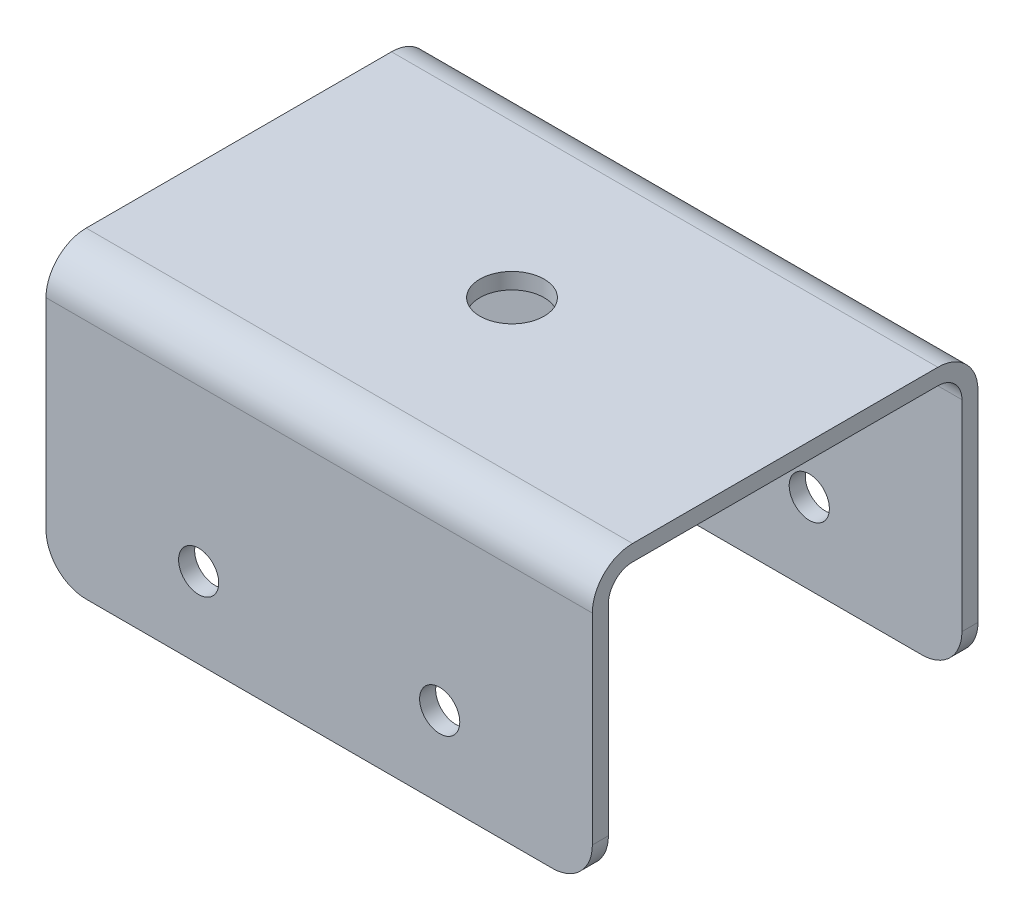
SolidWorks part; units mm, degrees
ref_plane "Front Plane" through (0, 0, 0) normal (0, 0, 1) x (1, 0, 0)
ref_plane "Top Plane" through (0, 0, 0) normal (0, 1, 0) x (1, 0, 0)
ref_plane "Right Plane" through (0, 0, 0) normal (1, 0, 0) x (0, 0, -1)
sketch "Sketch1" plane through (0, 0, 0) normal (0, 1, 0) x (1, 0, 0)
  line L1 (-34, 24) -> (34, 24)
  line L2 (-34, 24) -> (-34, -24)
  line L3 (-34, -24) -> (34, -24)
  line L4 (34, 24) -> (34, -24)
  line L5 (-34, 24) -> (34, -24) construction
  line L6 (-34, -24) -> (34, 24) construction
  point P0 (0, 0)
  dimension "D1" = 68
  dimension "D2" = 48
extrude "Boss-Extrude1" add sketch "Sketch1" along normal blind 35
shell "Shell1" thickness 2
fillet "Fillet1" radius 5 2 edges at (0, 35, -24) (0, 35, 24)
fillet "Fillet2" radius 3 2 edges at (0, 33, -22) (0, 33, 22)
sketch "Sketch2" plane through (-32, 0, 0) normal (1, 0, 0) x (0, 0, -1)
  line L4 (22, 0) -> (22, 30)
  line L5 (19, 33) -> (-19, 33)
  line L6 (-22, 30) -> (-22, 0)
  line L7 (-22, 0) -> (22, 0)
  line L8 (22, 0) -> (22, 30)
  line L9 (19, 33) -> (-19, 33)
  line L10 (-22, 30) -> (-22, 0)
  line L11 (-22, 0) -> (22, 0)
  arc A2 (22, 30) -> (19, 33) centre (19, 30) ccw
  arc A3 (22, 30) -> (19, 33) centre (19, 30) ccw
  arc A6 (-19, 33) -> (-22, 30) centre (-19, 30) ccw
  arc A7 (-19, 33) -> (-22, 30) centre (-19, 30) ccw
  dimension "D1" = 0
extrude "Cut-Extrude1" cut sketch "Sketch2" against normal up to next and the other way up to next
sketch "Sketch3" plane through (0, 0, 0) normal (0, 0, 1) x (1, 0, 0)
  line L0 (-34, 35) -> (34, 35) construction
  circle A0 centre (-15, 10) radius 2.5
  circle A1 centre (15, 10) radius 2.5
  dimension "D1" = 5
  dimension "D2" = 5
  dimension "D3" = 15
  dimension "D4" = 30
  dimension "D5" = 25
extrude "Cut-Extrude2" cut sketch "Sketch3" against normal through all both and the other way through all
fillet "Fillet3" radius 5 4 edges at (34, 0, -23) (34, 0, 23) (-34, 0, -23) (-34, 0, 23)
sketch "Sketch4" plane through (0, 35, 0) normal (0, 1, 0) x (1, 0, 0)
  circle A0 centre (0, 0) radius 4
  dimension "D1" = 8
extrude "Cut-Extrude3" cut sketch "Sketch4" against normal through all
